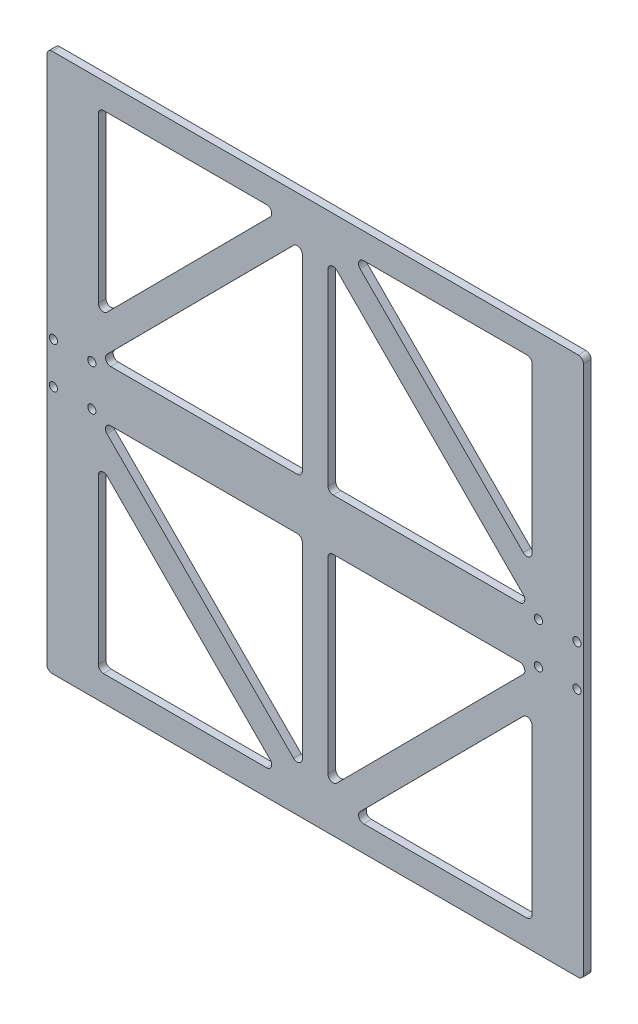
SolidWorks part; units mm, degrees
ref_plane "前视基准面" through (0, 0, 0) normal (0, 0, 1) x (1, 0, 0)
ref_plane "上视基准面" through (0, 0, 0) normal (0, 1, 0) x (1, 0, 0)
ref_plane "右视基准面" through (0, 0, 0) normal (1, 0, 0) x (0, 0, -1)
sketch "草图1" plane through (0, 0, 0) normal (0, 0, 1) x (1, 0, 0)
  line L0 (0, 105) -> (209, 105) construction
  line L1 (2, 0) -> (207, 0)
  line L2 (0, 2) -> (0, 208)
  line L3 (2, 210) -> (207, 210)
  line L4 (209, 2) -> (209, 208)
  line L5 (104.5, 210) -> (104.5, 0) construction
  line L6 (24.8084, 95) -> (97.5, 95)
  line L7 (23.39, 91.59) -> (96.0816, 18.4682)
  line L8 (112.9184, 18.4682) -> (185.61, 91.59)
  line L9 (184.1916, 95) -> (111.5, 95)
  line L10 (20, 75.9673) -> (20, 12)
  line L11 (22, 10) -> (85.591, 10)
  line L12 (87.0094, 13.41) -> (23.4184, 77.3774)
  line L13 (121.9906, 13.41) -> (185.5816, 77.3774)
  line L14 (189, 75.9673) -> (189, 12)
  line L15 (187, 10) -> (123.409, 10)
  line L16 (187, 200) -> (123.409, 200)
  line L17 (189, 134.0327) -> (189, 198)
  line L18 (121.9906, 196.59) -> (185.5816, 132.6226)
  line L19 (87.0094, 196.59) -> (23.4184, 132.6226)
  line L20 (22, 200) -> (85.591, 200)
  line L21 (20, 134.0327) -> (20, 198)
  line L22 (184.1916, 115) -> (111.5, 115)
  line L23 (112.9184, 191.5318) -> (185.61, 118.41)
  line L24 (23.39, 118.41) -> (96.0816, 191.5318)
  line L25 (24.8084, 115) -> (97.5, 115)
  line L26 (10, 105) -> (10, 93.3059) construction
  line L27 (109.5, 93) -> (109.5, 19.8782)
  line L28 (99.5, 93) -> (99.5, 19.8782)
  line L29 (99.5, 190.1218) -> (99.5, 117)
  line L31 (109.5, 190.1218) -> (109.5, 117)
  circle A0 centre (2.5, 97) radius 1.6
  circle A1 centre (17.5, 97) radius 1.6
  circle A2 centre (17.5, 113) radius 1.6
  circle A3 centre (2.5, 113) radius 1.6
  circle A4 centre (206.5, 97) radius 1.6
  circle A5 centre (191.5, 97) radius 1.6
  circle A6 centre (191.5, 113) radius 1.6
  circle A7 centre (206.5, 113) radius 1.6
  arc A8 (184.1916, 115) -> (185.61, 118.41) centre (184.1916, 117) ccw
  arc A9 (189, 134.0327) -> (185.5816, 132.6226) centre (187, 134.0327) cw
  arc A10 (187, 200) -> (189, 198) centre (187, 198) cw
  arc A11 (123.409, 200) -> (121.9906, 196.59) centre (123.409, 198) ccw
  arc A12 (111.5, 115) -> (109.5, 117) centre (111.5, 117) cw
  arc A13 (109.5, 190.1218) -> (112.9184, 191.5318) centre (111.5, 190.1218) cw
  arc A14 (23.4184, 132.6226) -> (20, 134.0327) centre (22, 134.0327) cw
  arc A15 (23.39, 118.41) -> (24.8084, 115) centre (24.8084, 117) ccw
  arc A16 (97.5, 115) -> (99.5, 117) centre (97.5, 117) ccw
  arc A17 (99.5, 190.1218) -> (96.0816, 191.5318) centre (97.5, 190.1218) ccw
  arc A18 (87.0094, 196.59) -> (85.591, 200) centre (85.591, 198) ccw
  arc A19 (22, 200) -> (20, 198) centre (22, 198) ccw
  arc A20 (185.5816, 77.3774) -> (189, 75.9673) centre (187, 75.9673) cw
  arc A21 (189, 12) -> (187, 10) centre (187, 12) cw
  arc A22 (121.9906, 13.41) -> (123.409, 10) centre (123.409, 12) ccw
  arc A23 (112.9184, 18.4682) -> (109.5, 19.8782) centre (111.5, 19.8782) cw
  arc A24 (109.5, 93) -> (111.5, 95) centre (111.5, 93) cw
  arc A25 (185.61, 91.59) -> (184.1916, 95) centre (184.1916, 93) ccw
  arc A26 (99.5, 93) -> (97.5, 95) centre (97.5, 93) ccw
  arc A27 (99.5, 19.8782) -> (96.0816, 18.4682) centre (97.5, 19.8782) cw
  arc A28 (85.591, 10) -> (87.0094, 13.41) centre (85.591, 12) ccw
  arc A29 (20, 12) -> (22, 10) centre (22, 12) ccw
  arc A30 (20, 75.9673) -> (23.4184, 77.3774) centre (22, 75.9673) cw
  arc A31 (24.8084, 95) -> (23.39, 91.59) centre (24.8084, 93) ccw
  arc A32 (2, 0) -> (0, 2) centre (2, 2) cw
  arc A33 (207, 0) -> (209, 2) centre (207, 2) ccw
  arc A34 (207, 210) -> (209, 208) centre (207, 208) cw
  arc A35 (0, 208) -> (2, 210) centre (2, 208) cw
  point P49 (189, 115)
  point P56 (189, 129.184)
  point P59 (189, 200)
  point P62 (118.6006, 200)
  point P69 (20, 129.184)
  point P72 (20, 115)
  point P79 (90.3994, 200)
  point P82 (20, 200)
  point P85 (189, 80.816)
  point P88 (189, 10)
  point P91 (118.6006, 10)
  point P98 (189, 95)
  point P105 (90.3994, 10)
  point P108 (20, 10)
  point P111 (20, 80.816)
  point P114 (20, 95)
  point P117 (0, 0)
  point P122 (209, 210)
  point P125 (0, 210)
  dimension "D7" = 3.2
  dimension "D8" = 3.2
  dimension "D13" = 2
  dimension "D14" = 2
  dimension "D15" = 2
  dimension "D1" = 209
  dimension "D2" = 210
  dimension "D3" = 20
  dimension "D4" = 10
  dimension "D5" = 10
  dimension "D6" = 20
  dimension "D9" = 16
  dimension "D10" = 15
  dimension "D11" = 10
  dimension "D12" = 10
extrude "凸台-拉伸1" add sketch "草图1" along normal blind 3
